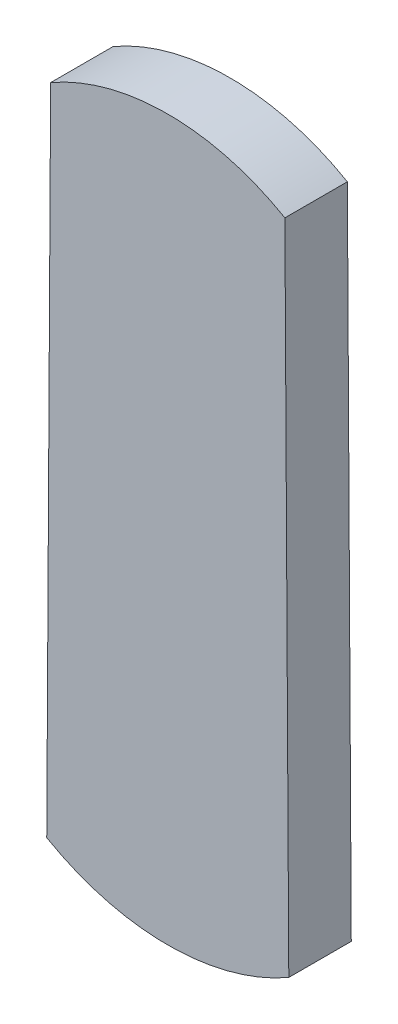
SolidWorks part; units mm, degrees
ref_plane "Front Plane" through (0, 0, 0) normal (0, 0, 1) x (1, 0, 0)
ref_plane "Top Plane" through (0, 0, 0) normal (0, 1, 0) x (1, 0, 0)
ref_plane "Right Plane" through (0, 0, 0) normal (1, 0, 0) x (0, 0, -1)
sketch "Sketch1" plane through (0, 0, 0) normal (0, 0, 1) x (1, 0, 0)
  line L0 (0, 0) -> (0, -90.1877) construction
  line L1 (-15, -4.0192) -> (-15.5, -88.0192)
  line L2 (15, -4.0192) -> (15.5, -88.0192)
  arc A0 (15, -4.0192) -> (-15, -4.0192) centre (0, -30) ccw
  arc A1 (15.5, -88.0192) -> (-15.5, -88.0192) centre (0, -61.1725) cw
  point P9 (-15.5, -8.7406)
  point P10 (0, 0)
  point P11 (0, 0)
  dimension "D3" = 30
  dimension "D4" = 31
  dimension "D1" = 30
  dimension "D2" = 31
  dimension "D5" = 84
extrude "Boss-Extrude1" add sketch "Sketch1" along normal blind 8
